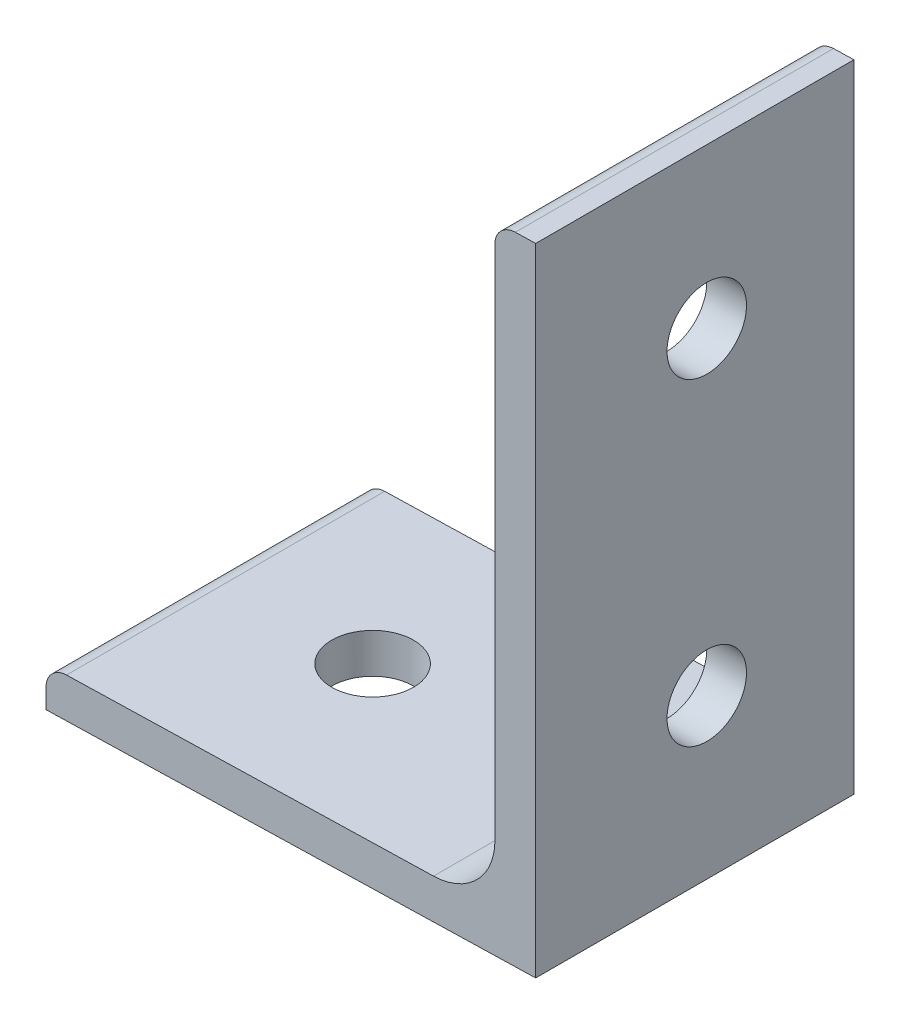
SolidWorks part; units mm, degrees
ref_plane "Front Plane" through (0, 0, 0) normal (0, 0, 1) x (1, 0, 0)
ref_plane "Top Plane" through (0, 0, 0) normal (0, 1, 0) x (1, 0, 0)
ref_plane "Right Plane" through (0, 0, 0) normal (1, 0, 0) x (0, 0, -1)
sketch "Sketch0" plane through (0, 0, 0) normal (0, 0, 1) x (1, 0, 0)
  line L0 (-19.05, -25.4) -> (19.05, -25.4)
  line L1 (19.05, -25.4) -> (19.05, 25.4)
  line L2 (19.05, 0) -> (0, 0) construction
  line L3 (0, 0) -> (0, -25.4) construction
  line L4 (15.875, -17.4498) -> (15.875, 25.4) construction
  line L5 (11.0998, -22.225) -> (-19.05, -22.225) construction
  arc A0 (15.875, -17.4498) -> (11.0998, -22.225) centre (11.0998, -17.4498) cw
  point P3 (14.4764, -20.8264)
  dimension "Inside Corner Radius" = 4.7752
  dimension "Outside Height" = 50.8
  dimension "Inside Height" = 47.625
  dimension "Inside Width" = 34.925
  dimension "Wall Thickness" = 3.175
  dimension "D1" = 3.175
  dimension "Outside Width" = 38.1
sketch "Sketch1" plane through (0, 0, 0) normal (1, 0, 0) x (0, 0, -1)
  line L0 (15.875, 0) -> (-15.875, 0)
  point P4 (0, 0)
  dimension "Length" = 31.75
sketch "Sketch2" plane through (0, 0, 0) normal (0, 0, 1) x (1, 0, 0)
  line L0 (-19.05, -25.4) -> (19.05, -25.4)
  line L1 (19.05, -25.4) -> (19.05, 25.4)
  line L2 (19.05, 25.4) -> (15.875, 25.4) construction
  line L3 (15.875, 23.8125) -> (15.875, -17.4498)
  line L4 (11.0998, -22.225) -> (-17.4625, -22.225)
  line L5 (-19.05, -25.4) -> (-19.05, -22.225) construction
  line L6 (17.4625, 25.4) -> (19.05, 25.4)
  line L7 (-19.05, -23.8125) -> (-19.05, -25.4)
  line L8 (19.05, 0) -> (0, 0) construction
  line L9 (0, 0) -> (0, -25.4) construction
  arc A0 (15.875, 23.8125) -> (17.4625, 25.4) centre (17.4625, 23.8125) cw
  arc A1 (-19.05, -23.8125) -> (-17.4625, -22.225) centre (-17.4625, -23.8125) cw
  arc A2 (15.875, -17.4498) -> (11.0998, -22.225) centre (11.0998, -17.4498) cw
  dimension "Inside Radius" = 4.7752
  dimension "Height" = 50.8
  dimension "Width" = 38.1
  dimension "Thickness" = 3.175
extrude "Boss-Extrude1" add sketch "Sketch2" along normal mid plane 31.75
sketch "Break Locations" plane through (0, 0, 0) normal (1, 0, 0) x (0, 0, -1)
  line L0 (35.941, 0) -> (-35.941, 0)
  line L1 (-15.875, -25.4) -> (-15.875, 25.4) construction
  line L2 (15.875, -25.4) -> (15.875, 25.4) construction
  point P0 (27.305, 0)
  point P1 (-27.305, 0)
  point P10 (0, 0)
  point P11 (-35.941, 0)
  point P13 (35.941, 0)
  dimension "D1" = 43.18
  dimension "D2" = 43.18
  dimension "D3" = 51.816
sketch "Sketch3" plane through (0, -25.4, 0) normal (0, -1, 0) x (1, 0, 0)
  line L0 (-19.05, -13.9268) -> (19.05, -14.9245)
  line L1 (19.05, 15.875) -> (19.05, -15.875) construction
  line L2 (19.05, -14.9245) -> (15.875, -14.811) construction
  line L4 (-19.05, 11.4819) -> (19.05, 10.4842)
  line L5 (19.05, 10.4842) -> (19.05, -14.9245)
  line L6 (-19.05, -13.9268) -> (-19.05, 11.4819)
sketch "Sketch4" plane through (19.05, 0, 0) normal (1, 0, 0) x (0, 0, -1)
  line L0 (15.875, -25.4) -> (3.175, -25.4) construction
  line L1 (-15.875, -25.4) -> (15.875, -25.4) construction
  line L2 (3.175, -25.4) -> (3.175, -12.7) construction
  line L3 (3.175, -12.7) -> (3.175, 12.7) construction
  circle A0 centre (3.175, 12.7) radius 3.175
  circle A1 centre (3.175, -12.7) radius 3.175
  dimension "D1" = 12.7
  dimension "D2" = 12.7
  dimension "D3" = 25.4
extrude "Cut-Extrude1" cut sketch "Sketch4" against normal through all
extrude "Cut-Extrude2" cut sketch "Sketch3" against normal through all flip side to cut
hole_wizard "1/4 Clearance Hole1" positions "Sketch7" profile "Sketch8" hole size "1/4" standard "ANSI Inch" end condition through all
sketch "Sketch7" plane through (0, -25.4, 0) normal (0, -1, 0) x (-1, 0, 0)
  point P0 (6.0219, 1.5636)
sketch "Sketch8" plane through (-6.0219, -25.4, -1.5636) normal (1, 0, 0) x (0, 0, -1)
  line L0 (0, 0) -> (0, 50.8)
  line L1 (0, 50.8) -> (3.2639, 50.8)
  line L2 (3.2639, 50.8) -> (3.2639, 0)
  line L5 (3.2639, 0) -> (0, 0)
  line L11 (0, -6.35) -> (0, 107.95) construction
  dimension "Thru Hole Dia." = 6.5278
  dimension "Thru Hole Depth" = 50.8
sketch "Sketch9" plane through (15.875, 0, 0) normal (-1, 0, 0) x (0, 0, 1)
  circle A0 centre (-3.175, -12.7) radius 6.35
extrude "Cut-Extrude3" cut sketch "Sketch9" along normal blind 2.54
equation "\"D1@Break Locations\" = .85 * \"Height@Sketch2\""
equation "\"D2@Break Locations\"=\"D1@Break Locations\""
equation "\"Thickness@Sketch2\"=\"wall thickness@sketch0\""
equation "\"Height@Sketch2\"=\"outside height@sketch0\""
equation "\"Width@Sketch2\"=\"outside width@sketch0\""
equation "\"Inside Radius@Sketch2\"=\"inside corner radius@sketch0\""
equation "\"Length@Boss-Extrude1\"=\"length@sketch1\""
equation "\"D3@Break Locations\"=\"D2@Break Locations\"*1.2"
equation "\"D1@Sketch0\"=\"Wall Thickness@Sketch0\""
